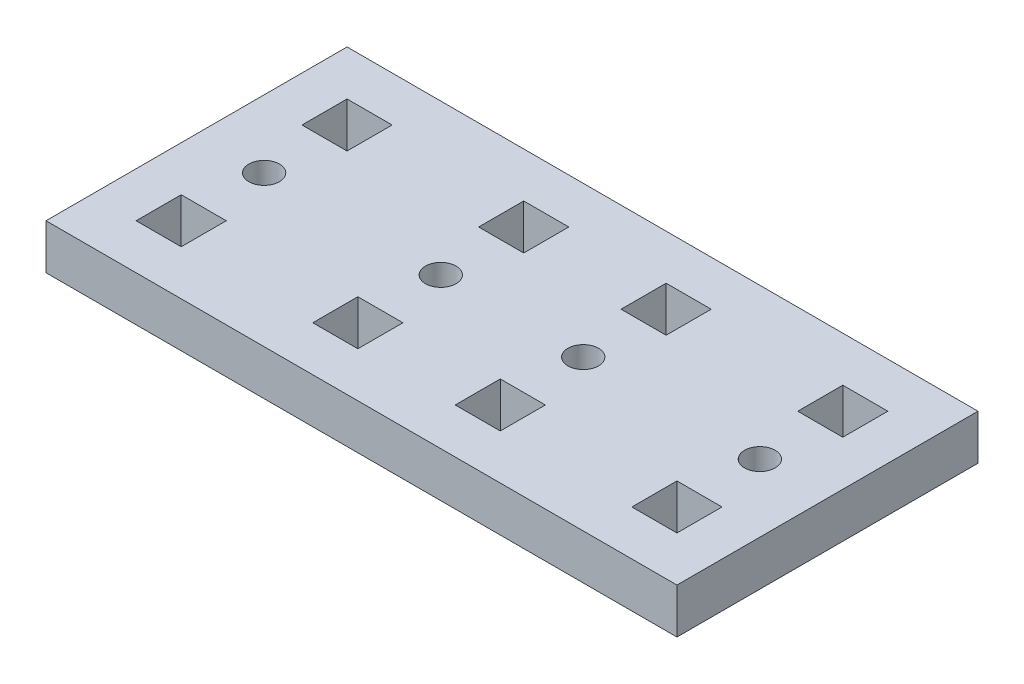
SolidWorks part; units mm, degrees
ref_plane "Front Plane" through (0, 0, 0) normal (0, 0, 1) x (1, 0, 0)
ref_plane "Top Plane" through (0, 0, 0) normal (0, 1, 0) x (1, 0, 0)
ref_plane "Right Plane" through (0, 0, 0) normal (1, 0, 0) x (0, 0, -1)
sketch "Elevator Spacer" plane through (0, 0, 0) normal (0, 1, 0) x (1, 0, 0)
  line L0 (0, 21.209) -> (0, -21.209) construction
  line L1 (-44.45, -21.209) -> (44.45, -21.209)
  line L2 (-44.45, -21.209) -> (-44.45, 21.209)
  line L3 (-44.45, 21.209) -> (44.45, 21.209)
  line L4 (44.45, -21.209) -> (44.45, 21.209)
  line L5 (-44.45, -21.209) -> (44.45, 21.209) construction
  line L6 (-44.45, 21.209) -> (44.45, -21.209) construction
  line L7 (-44.45, 0) -> (44.45, 0) construction
  line L8 (34.925, -14.859) -> (34.925, 14.859) construction
  line L9 (32.766, 0) -> (37.084, 0) construction
  line L10 (31.75, 8.509) -> (38.1, 8.509)
  line L11 (31.75, 8.509) -> (31.75, 14.859)
  line L12 (31.75, 14.859) -> (38.1, 14.859)
  line L13 (38.1, 8.509) -> (38.1, 14.859)
  line L14 (31.75, 8.509) -> (38.1, 14.859) construction
  line L15 (31.75, 14.859) -> (38.1, 8.509) construction
  line L16 (31.75, -14.859) -> (38.1, -8.509) construction
  line L17 (31.75, -8.509) -> (38.1, -14.859) construction
  line L18 (38.1, -8.509) -> (38.1, -14.859)
  line L19 (31.75, -14.859) -> (38.1, -14.859)
  line L20 (31.75, -8.509) -> (31.75, -14.859)
  line L21 (31.75, -8.509) -> (38.1, -8.509)
  line L22 (10.033, -14.859) -> (10.033, 14.859) construction
  line L23 (7.874, 0) -> (12.192, 0) construction
  line L24 (6.858, 8.509) -> (13.208, 8.509)
  line L25 (6.858, 8.509) -> (6.858, 14.859)
  line L26 (6.858, 14.859) -> (13.208, 14.859)
  line L27 (13.208, 8.509) -> (13.208, 14.859)
  line L28 (6.858, 8.509) -> (13.208, 14.859) construction
  line L29 (6.858, 14.859) -> (13.208, 8.509) construction
  line L30 (6.858, -14.859) -> (13.208, -8.509) construction
  line L31 (6.858, -8.509) -> (13.208, -14.859) construction
  line L32 (13.208, -8.509) -> (13.208, -14.859)
  line L33 (6.858, -14.859) -> (13.208, -14.859)
  line L34 (6.858, -8.509) -> (6.858, -14.859)
  line L35 (6.858, -8.509) -> (13.208, -8.509)
  line L36 (-6.858, -8.509) -> (-13.208, -14.859) construction
  line L37 (-6.858, -14.859) -> (-13.208, -8.509) construction
  line L38 (-6.858, 14.859) -> (-13.208, 8.509) construction
  line L39 (-6.858, 8.509) -> (-13.208, 14.859) construction
  line L40 (-7.874, 0) -> (-12.192, 0) construction
  line L41 (-10.033, -14.859) -> (-10.033, 14.859) construction
  line L42 (-31.75, -8.509) -> (-38.1, -14.859) construction
  line L43 (-31.75, -14.859) -> (-38.1, -8.509) construction
  line L44 (-31.75, 14.859) -> (-38.1, 8.509) construction
  line L45 (-31.75, 8.509) -> (-38.1, 14.859) construction
  line L46 (-32.766, 0) -> (-37.084, 0) construction
  line L47 (-34.925, -14.859) -> (-34.925, 14.859) construction
  line L48 (-6.858, -8.509) -> (-13.208, -8.509)
  line L49 (-6.858, -8.509) -> (-6.858, -14.859)
  line L50 (-6.858, -14.859) -> (-13.208, -14.859)
  line L51 (-13.208, -8.509) -> (-13.208, -14.859)
  line L52 (-13.208, 8.509) -> (-13.208, 14.859)
  line L53 (-6.858, 14.859) -> (-13.208, 14.859)
  line L54 (-6.858, 8.509) -> (-6.858, 14.859)
  line L55 (-6.858, 8.509) -> (-13.208, 8.509)
  line L56 (-31.75, -8.509) -> (-38.1, -8.509)
  line L57 (-31.75, -8.509) -> (-31.75, -14.859)
  line L58 (-31.75, -14.859) -> (-38.1, -14.859)
  line L59 (-38.1, -8.509) -> (-38.1, -14.859)
  line L60 (-38.1, 8.509) -> (-38.1, 14.859)
  line L61 (-31.75, 14.859) -> (-38.1, 14.859)
  line L62 (-31.75, 8.509) -> (-31.75, 14.859)
  line L63 (-31.75, 8.509) -> (-38.1, 8.509)
  circle A0 centre (34.925, 0) radius 2.159
  circle A1 centre (10.033, 0) radius 2.159
  circle A2 centre (-10.033, 0) radius 2.159
  circle A3 centre (-34.925, 0) radius 2.159
  point P0 (0, 0)
  point P12 (34.925, 11.684)
  point P25 (34.925, -11.684)
  point P28 (10.033, 11.684)
  point P41 (10.033, -11.684)
  point P70 (-10.033, -11.684)
  point P71 (-10.033, 11.684)
  point P72 (-34.925, -11.684)
  point P73 (-34.925, 11.684)
  dimension "D4" = 4.318
  dimension "D8" = 4.318
  dimension "D1" = 6.35
  dimension "D2" = 6.35
  dimension "D3" = 6.35
  dimension "D5" = 6.35
  dimension "D6" = 6.35
  dimension "D7" = 6.35
  dimension "D9" = 6.858
  dimension "D10" = 31.75
  dimension "D11" = 6.35
  dimension "D12" = 6.35
extrude "Boss-Extrude1" add sketch "Elevator Spacer" along normal blind 6.35
equation "\"Ball Diameter\"= 1.75in"
equation "\"Sheet Thickness\"= 0.25in"
equation "\"Screw Diameter\"= .17in"
equation "\"Robot Diameter\"= 14in"
equation "\"Castor Screw Diameter\"= 0.22in"
equation "\"Wheel Diameter\" = 4in"
equation "\"Nut Diameter\" = 8.4mm"
equation "\"Nut Height\" = 2.9mm"
equation "\"Screw Height\" = 0.55in"
equation "\"Pulley Diameter\" = 1in"
equation "\"Reactor Height\" = 14in"
equation "\"Elevator Height\" = 11.5in"
equation "\"Elevator Width\" = \"Ball Diameter\" + 0.25in"
equation "\"Elevator Bearing Diameter\" = sqr(2*(\"Sheet Thickness\"^2)) + 0.2in"
equation "\"Elevator Axle Endcap Diameter\" = \"Pulley Diameter\" + 0.25in"
equation "\"Elevator Axle Length\" = \"Elevator Width\" + 8*\"Sheet Thickness\""
equation "\"Elevator Clearance from Axis\" = 3.28in"
equation "\"D1@Boss-Extrude1\"=\"Sheet Thickness\""
